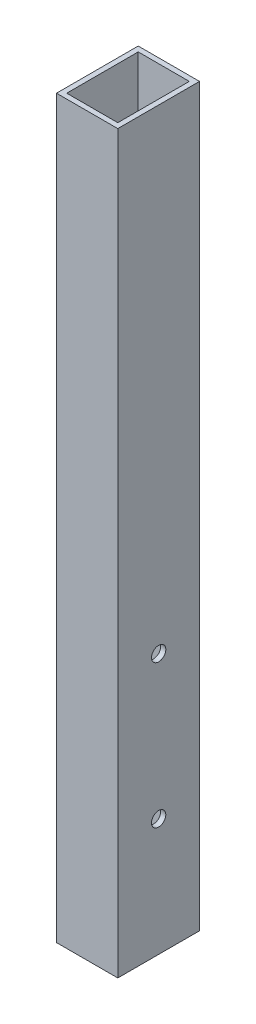
SolidWorks part; units mm, degrees
material "AISI 304"
ref_plane "Front Plane" through (0, 0, 0) normal (0, 0, 1) x (1, 0, 0)
ref_plane "Top Plane" through (0, 0, 0) normal (0, 1, 0) x (1, 0, 0)
ref_plane "Right Plane" through (0, 0, 0) normal (1, 0, 0) x (0, 0, -1)
sketch "Sketch1" plane through (0, 0, 0) normal (0, 1, 0) x (1, 0, 0)
  line L1 (-38.1, -50.8) -> (38.1, -50.8)
  line L2 (-38.1, -50.8) -> (-38.1, 50.8)
  line L3 (-38.1, 50.8) -> (38.1, 50.8)
  line L4 (38.1, -50.8) -> (38.1, 50.8)
  line L5 (-38.1, -50.8) -> (38.1, 50.8) construction
  line L6 (-38.1, 50.8) -> (38.1, -50.8) construction
  point P0 (0, 0)
  dimension "D1" = 101.6
  dimension "D2" = 76.2
extrude "Boss-Extrude1" add sketch "Sketch1" along normal blind 914.4
sketch "Sketch2" plane through (0, 914.4, 0) normal (0, 1, 0) x (1, 0, 0)
  line L0 (-38.1, 50.8) -> (-38.1, -50.8) construction
  line L1 (-31.75, -44.45) -> (31.75, -44.45)
  line L2 (-31.75, -44.45) -> (-31.75, 44.45)
  line L3 (-31.75, 44.45) -> (31.75, 44.45)
  line L4 (31.75, -44.45) -> (31.75, 44.45)
  line L5 (-31.75, -44.45) -> (31.75, 44.45) construction
  line L6 (-31.75, 44.45) -> (31.75, -44.45) construction
  line L7 (38.1, -50.8) -> (38.1, 50.8) construction
  line L8 (38.1, 50.8) -> (-38.1, 50.8) construction
  line L9 (-38.1, -50.8) -> (38.1, -50.8) construction
  point P0 (0, 0)
  dimension "D1" = 6.35
  dimension "D2" = 6.35
  dimension "D3" = 6.35
  dimension "D4" = 6.35
extrude "Cut-Extrude1" cut sketch "Sketch2" against normal through all
sketch "Sketch3" plane through (-38.1, 0, 0) normal (-1, 0, 0) x (0, 0, 1)
  line L0 (-50.8, 0) -> (50.8, 0) construction
  circle A0 centre (0, 146.05) radius 8.89
  circle A1 centre (0, 323.85) radius 8.89
  dimension "D1" = 17.78
  dimension "D2" = 17.78
  dimension "D3" = 177.8
  dimension "D4" = 146.05
extrude "Cut-Extrude2" cut sketch "Sketch3" against normal through all
